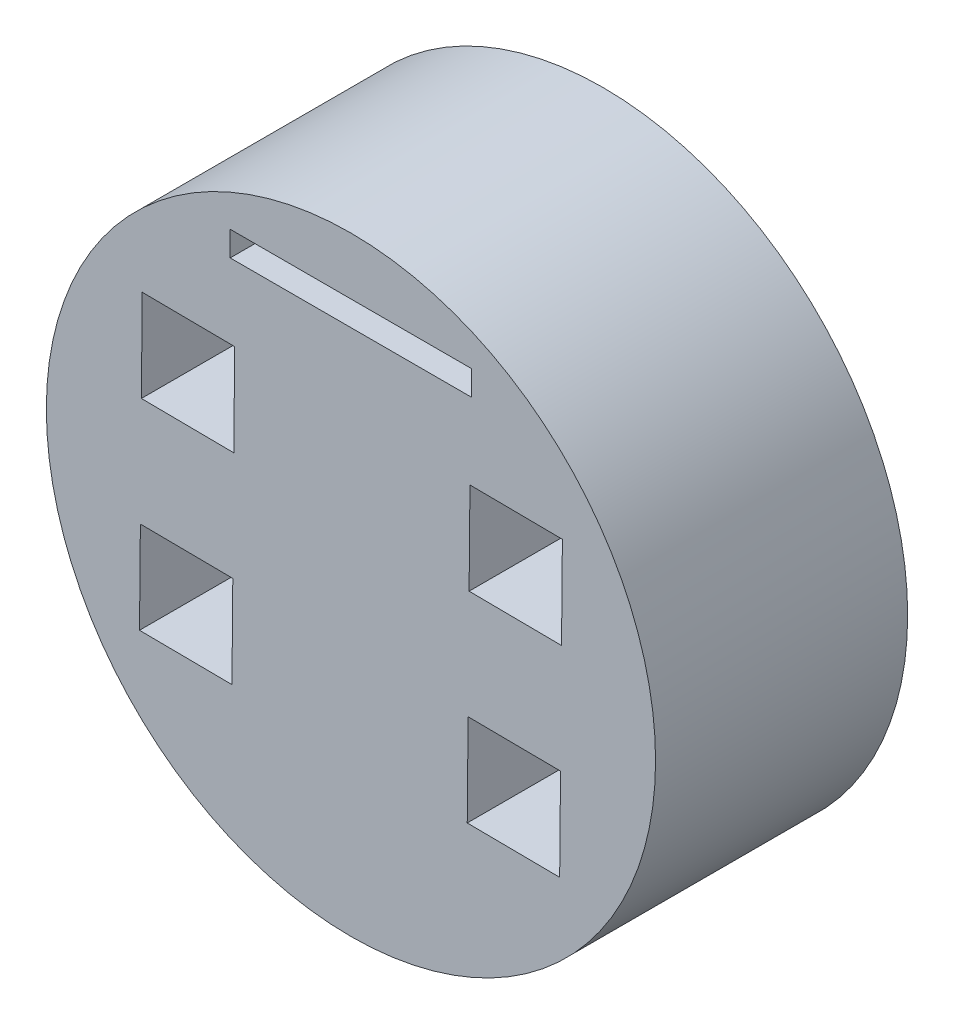
SolidWorks part; units mm, degrees
material "Polyurethane Foam Flexible"
ref_plane "Front Plane" through (0, 0, 0) normal (0, 0, 1) x (1, 0, 0)
ref_plane "Top Plane" through (0, 0, 0) normal (0, 1, 0) x (1, 0, 0)
ref_plane "Right Plane" through (0, 0, 0) normal (1, 0, 0) x (0, 0, -1)
sketch "Sketch1" plane through (0, 0, 0) normal (0, 0, 1) x (1, 0, 0)
  circle A0 centre (0, 0) radius 92.075
  dimension "D1" = 184.15
extrude "Boss-Extrude1" add sketch "Sketch1" along normal blind 76.2
sketch "Sketch7" plane through (0, 0, 0) normal (0, 0, -1) x (-1, 0, 0)
  line L8 (35.1482, 44.7763) -> (35.4061, 16.8375)
  line L9 (63.087, 45.0342) -> (63.3449, 17.0954)
  line L10 (63.087, 45.0342) -> (35.1482, 44.7763)
  line L11 (63.3449, 17.0954) -> (35.4061, 16.8375)
  line L12 (63.6497, -15.9232) -> (35.7109, -16.1811)
  line L13 (63.9075, -43.862) -> (63.6497, -15.9232)
  line L14 (35.9687, -44.1199) -> (35.7109, -16.1811)
  line L15 (63.9075, -43.862) -> (35.9687, -44.1199)
  line L16 (0, 0) -> (-0.563, 61.0017) construction
  line L17 (-35.1482, -44.7763) -> (-35.4061, -16.8375)
  line L18 (-63.087, -45.0342) -> (-35.1482, -44.7763)
  line L19 (-63.087, -45.0342) -> (-63.3449, -17.0954)
  line L20 (-63.3449, -17.0954) -> (-35.4061, -16.8375)
  line L21 (-63.6497, 15.9232) -> (-35.7109, 16.1811)
  line L22 (-63.9075, 43.862) -> (-63.6497, 15.9232)
  line L23 (-63.9075, 43.862) -> (-35.9687, 44.1199)
  line L24 (-35.9687, 44.1199) -> (-35.7109, 16.1811)
extrude "Cut-Extrude3" cut sketch "Sketch7" against normal up to surface (76.2 mm away) up to face at (92.075, 0, 76.2)
sketch "Sketch8" plane through (0, 0, 76.2) normal (0, 0, 1) x (1, 0, 0)
  line L0 (0, 0) -> (0, 67.31) construction
  line L2 (-36.5, 74.81) -> (36.5, 74.81)
  line L3 (-36.5, 74.81) -> (-36.5, 67.31)
  line L4 (-36.5, 67.31) -> (36.5, 67.31)
  line L5 (36.5, 74.81) -> (36.5, 67.31)
  point P7 (0, 57.3735)
  point P8 (0, 67.31)
  dimension "D1" = 73
  dimension "D2" = 7.5
  dimension "D3" = 67.31
extrude "Cut-Extrude4" cut sketch "Sketch8" against normal up to surface (76.2 mm away) up to face at (49.8092, 30.0216, 0)
